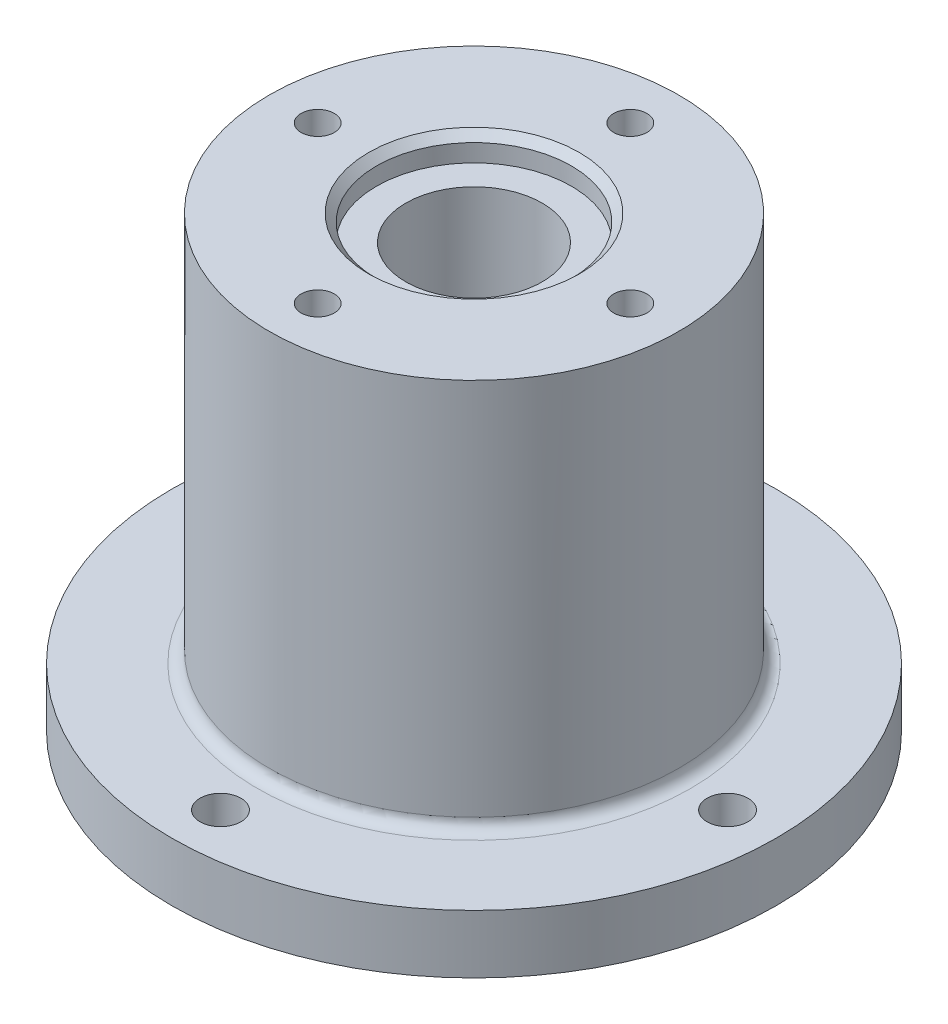
SolidWorks part; units mm, degrees
ref_plane "Front Plane" through (0, 0, 0) normal (0, 0, 1) x (1, 0, 0)
ref_plane "Top Plane" through (0, 0, 0) normal (0, 1, 0) x (1, 0, 0)
ref_plane "Right Plane" through (0, 0, 0) normal (1, 0, 0) x (0, 0, -1)
sketch "Sketch2" plane through (0, 0, 0) normal (0, 0, 1) x (1, 0, 0)
  line L0 (0, -0.7741) -> (0, -34.3158) construction
  line L1 (25, 115) -> (25, 108.5)
  line L2 (25, 108.5) -> (17.5, 108.5)
  line L3 (17.5, 108.5) -> (17.5, 51)
  line L4 (17.5, 51) -> (8, 51)
  line L5 (8, 51) -> (8, 35)
  line L8 (18.7361, 32.5) -> (37.5, 0)
  line L9 (37.5, 0) -> (77.5, 0)
  line L10 (77.5, 0) -> (77.5, 15)
  line L11 (77.5, 15) -> (52.5, 15)
  line L12 (52.5, 15) -> (52.5, 115)
  line L13 (52.5, 115) -> (25, 115)
  line L14 (8, 35) -> (14.406, 35)
  line L17 (38.225, 0) -> (-38.225, 0) construction
  line L19 (0, -63.25) -> (0, 63.25) construction
  arc A0 (14.406, 35) -> (18.7361, 32.5) centre (14.406, 30) cw
  dimension "D10" = 5
  dimension "D1" = 50
  dimension "D2" = 105
  dimension "D3" = 155
  dimension "D4" = 16
  dimension "D5" = 35
  dimension "D6" = 115
  dimension "D7" = 15
  dimension "D8" = 6.5
  dimension "D9" = 64
  dimension "D11" = 60
  dimension "D12" = 75
  dimension "D13" = 16
revolve "Revolve1" add sketch "Sketch2" angle 360 about L0
fillet "Fillet1" radius 3 1 edges at (-52.5, 15, 0)
fillet "Fillet2" radius 5 1 edges at (-37.5, 0, 0)
fillet "Fillet3" radius 2.5 1 edges at (-17.5, 51, 0)
chamfer "Chamfer1" distance 2 angle 45 1 edges at (-25, 115, 0)
hole_wizard "M10 Clearance Hole2" positions "Sketch10" profile "Sketch11" hole size "M10" standard "ISO" end condition through all
sketch "Sketch10" plane through (0, 15, 0) normal (0, 1, 0) x (1, 0, 0)
  line L0 (77.5, 0) -> (52.5, 0) construction
  line L1 (0, -63.25) -> (0, 63.25) construction
  line L2 (-63.25, 0) -> (63.25, 0) construction
  circle A1 centre (0, 0) radius 65 construction
  circle A2 centre (0, 0) radius 77.5 construction
  point P0 (0, 65)
  point P2 (65, 0)
  point P6 (0, -65)
  point P8 (-65, 0)
  dimension "D1" = 130
sketch "Sketch11" plane through (0, 15, -65) normal (1, 0, 0) x (0, 0, 1)
  line L0 (0, 0) -> (0, 15)
  line L1 (0, 15) -> (5.25, 15)
  line L2 (5.25, 15) -> (5.25, 0)
  line L5 (5.25, 0) -> (0, 0)
  line L11 (0, -6.35) -> (0, 107.95) construction
  dimension "Thru Hole Dia." = 10.5
  dimension "Thru Hole Depth" = 15
sketch "Esquisse1" plane through (0, 115, 0) normal (0, 1, 0) x (1, 0, 0)
  circle A0 centre (0, 0) radius 40 construction
  point P3 (-40, 0)
  dimension "D1" = 80
ref_point "Point1"
hole_wizard "Trou taraudé M101" positions "Esquisse4" profile "Esquisse5" tap size "M10" standard "ISO"
sketch "Esquisse4" plane through (0, 115, 0) normal (0, 1, 0) x (1, 0, 0)
  point P0 (-40.0726, 0)
sketch "Esquisse5" plane through (-40.0726, 115, 0) normal (1, 0, 0) x (0, 0, 1)
  line L0 (0, 0) -> (0, 30.0537)
  line L1 (0, 30.0537) -> (4.25, 27.5)
  line L2 (4.25, 27.5) -> (4.25, 0)
  line L5 (4.25, 0) -> (0, 0)
  line L10 (0, 30.0537) -> (-4.25, 27.5) construction
  line L11 (0, -6.35) -> (0, 107.95) construction
  dimension "Diamètre du trou pour taraudage" = 8.5
  dimension "Profondeur du trou pour taraudage" = 27.5
  dimension "Angle de pointe" = 118
cosmetic thread "Filetage de perçage1" parameters "D1"=20, "D2"=10
pattern_circular "Répétition circulaire1" count 4 every 90 about axis through (0, 0, 0) along (0, 1, 0) of "Trou taraudé M101"
cosmetic thread "Filetage de perçage2" parameters "D1"=20, "D2"=10
cosmetic thread "Filetage de perçage3" parameters "D1"=20, "D2"=10
cosmetic thread "Filetage de perçage4" parameters "D1"=20, "D2"=10
